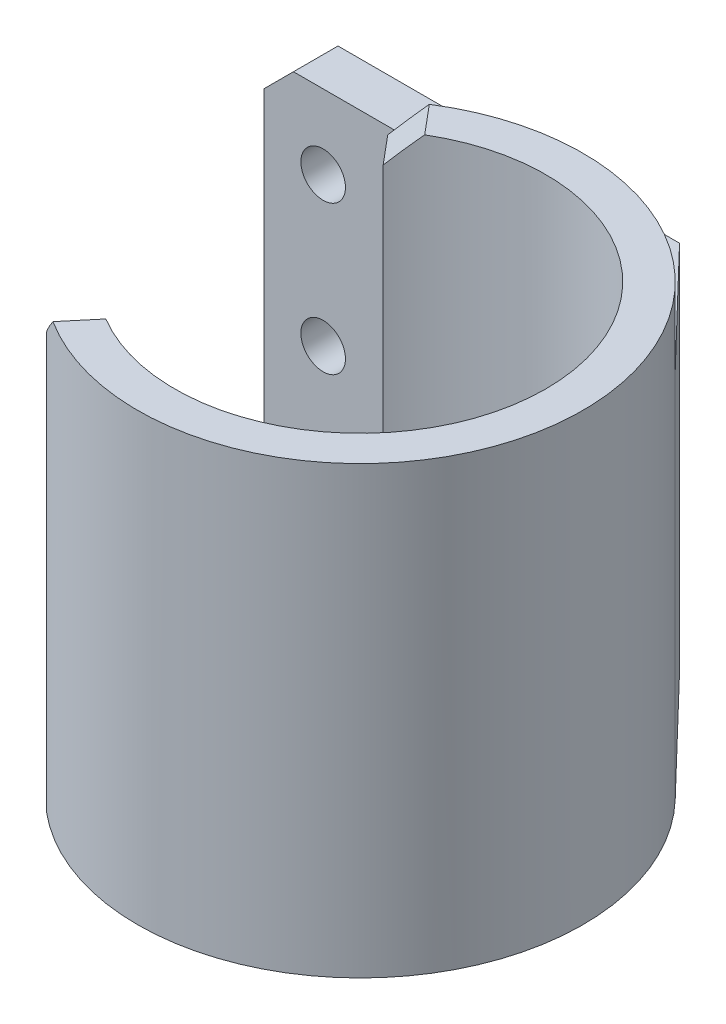
SolidWorks part; units mm, degrees
ref_plane "Front Plane" through (0, 0, 0) normal (0, 0, 1) x (1, 0, 0)
ref_plane "Top Plane" through (0, 0, 0) normal (0, 1, 0) x (1, 0, 0)
ref_plane "Right Plane" through (0, 0, 0) normal (1, 0, 0) x (0, 0, -1)
sketch "Sketch1" plane through (0, 0, 0) normal (0, 1, 0) x (1, 0, 0)
  circle A0 centre (0, 0) radius 15
  circle A1 centre (0, 0) radius 6.25
  dimension "D1" = 12.5
  dimension "D2" = 30
extrude "Boss-Extrude1" add sketch "Sketch1" along normal blind 10
sketch "Sketch2" plane through (0, 10, 0) normal (0, 1, 0) x (1, 0, 0)
  circle A0 centre (0, 0) radius 15
  circle A1 centre (0, 0) radius 12.5
  circle A3 centre (0, 0) radius 15 construction
  dimension "D1" = 25
extrude "Boss-Extrude2" add sketch "Sketch2" along normal blind 20
sketch "Sketch3" plane through (0, 0, 0) normal (0, 1, 0) x (1, 0, 0)
  line L0 (0, 0) -> (-9.6418, 11.4907)
  line L1 (0, 0) -> (-9.6418, -11.4907)
  line L2 (0, 0) -> (-15, 0) construction
  circle A0 centre (0, 0) radius 15 construction
  arc A1 (-9.6418, 11.4907) -> (-9.6418, -11.4907) centre (0, 0) ccw
  dimension "D1" = 100
extrude "Cut-Extrude1" cut sketch "Sketch3" along normal through all
sketch "Sketch4" plane through (0, 0, 0) normal (0, 1, 0) x (1, 0, 0)
  line L0 (-9.6418, 11.4907) -> (-9.6418, 15)
  line L1 (-9.6418, 15) -> (-21.5, 15)
  line L2 (-21.5, 15) -> (-21.5, 18)
  line L3 (-21.5, 18) -> (3.5, 18)
  line L4 (3.5, 18) -> (10.8114, 10.3978)
  line L5 (0, 0) -> (-12.5, 0) construction
  arc A0 (-9.6418, -11.4907) -> (-9.6418, 11.4907) centre (0, 0) ccw construction
  arc A1 (10.8114, 10.3978) -> (-9.6418, 11.4907) centre (0, 0) ccw
  arc A2 (-8.0348, -9.5756) -> (-8.0348, 9.5756) centre (0, 0) ccw construction
  dimension "D1" = 9
  dimension "D2" = 3
  dimension "D3" = 15
  dimension "D4" = 25
extrude "Boss-Extrude3" add sketch "Sketch4" along normal blind 25
sketch "Sketch5" plane through (0, 0, -15) normal (0, 0, 1) x (1, 0, 0)
  line L0 (-21.5, 25) -> (-21.5, 0) construction
  line L1 (-17.5, 20) -> (-17.5, 10) construction
  line L3 (-21.5, 0) -> (-9.6418, 0) construction
  circle A0 centre (-17.5, 20) radius 1.5
  circle A1 centre (-17.5, 10) radius 1.5
  point P9 (-15.5709, 0)
  dimension "D2" = 3
  dimension "D1" = 4
  dimension "D3" = 10
  dimension "D4" = 10
extrude "Cut-Extrude2" cut sketch "Sketch5" against normal through all
sketch "Sketch6" plane through (0, 10, 0) normal (0, 1, 0) x (1, 0, 0)
  line L0 (0, 0) -> (-12.5, 0) construction
  line L1 (0, -6.25) -> (-12.5, -6.25)
  line L2 (0, 6.25) -> (-12.5, 6.25)
  arc A0 (0, -6.25) -> (0, 6.25) centre (0, 0) ccw
  arc A1 (-12.5, 6.25) -> (-12.5, -6.25) centre (-12.5, 0) ccw
  arc A2 (-4.0174, -4.7878) -> (-4.0174, 4.7878) centre (0, 0) ccw construction
  arc A3 (-8.0348, -9.5756) -> (-8.0348, 9.5756) centre (0, 0) ccw construction
  point P3 (-6.25, 0)
extrude "Cut-Extrude3" cut sketch "Sketch6" against normal through all
chamfer "Chamfer2" distance 2 angle 45 3 edges at (-8.8383, 30, 10.5331) (-8.8383, 30, -10.5331) (-21.5, 25, -16.5)
